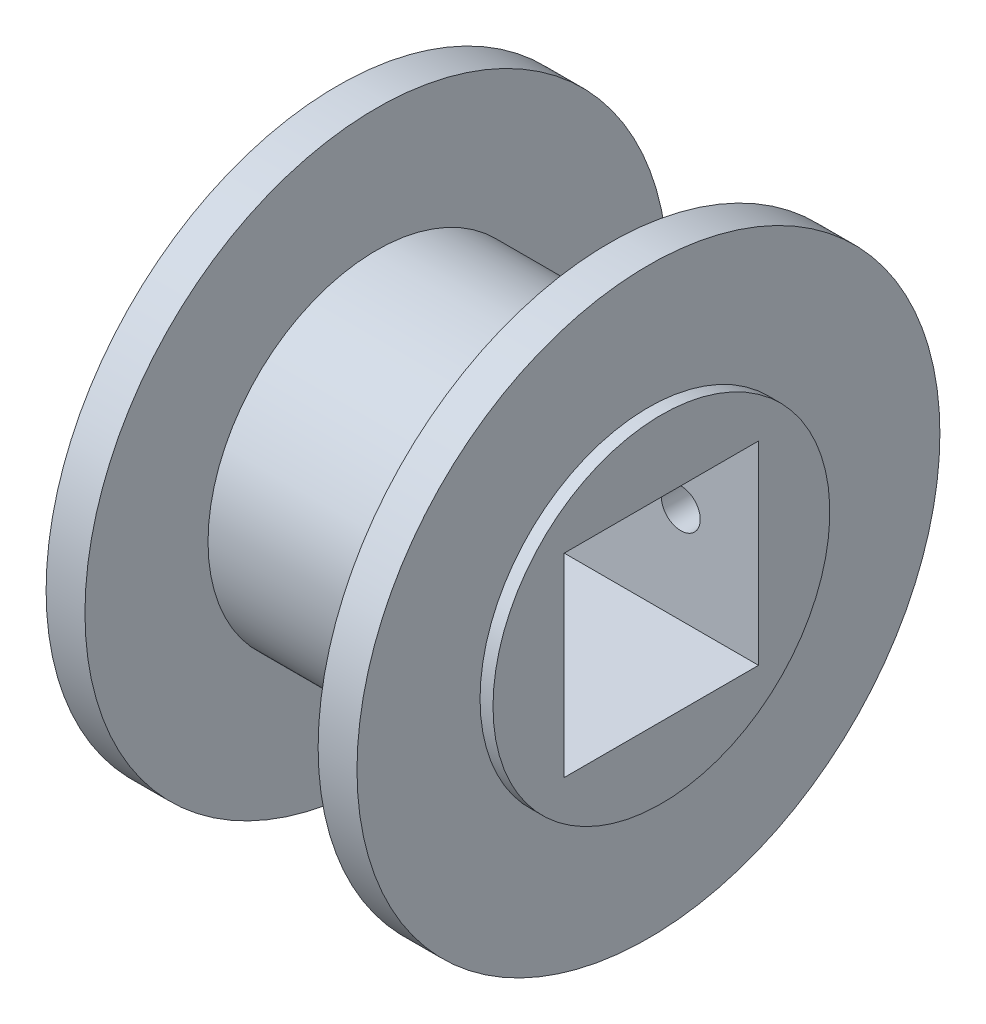
SolidWorks part; units mm, degrees
ref_plane "Front Plane" through (0, 0, 0) normal (0, 0, 1) x (1, 0, 0)
ref_plane "Top Plane" through (0, 0, 0) normal (0, 1, 0) x (1, 0, 0)
ref_plane "Right Plane" through (0, 0, 0) normal (1, 0, 0) x (0, 0, -1)
sketch "Sketch1" plane through (0, 0, 0) normal (0, 0, 1) x (1, 0, 0)
  line L0 (0, 0) -> (32.5033, 0) construction
  line L1 (0, 0) -> (0, 29.8727) construction
  line L2 (-13, -7.5) -> (13, -7.5) construction
  line L3 (-13, -7.5) -> (-13, 7.5) construction
  line L4 (-13, 7.5) -> (13, 7.5)
  line L5 (13, -7.5) -> (13, 7.5) construction
  line L6 (-13, -7.5) -> (13, 7.5) construction
  line L7 (-13, 7.5) -> (13, -7.5) construction
  line L8 (-13, 7.5) -> (-13, 13)
  line L9 (-13, 13) -> (-12, 13)
  line L10 (-12, 13) -> (-12, 22.5)
  line L11 (-12, 22.5) -> (-9, 22.5)
  line L12 (-9, 22.5) -> (-9, 13)
  line L13 (-9, 13) -> (9, 13)
  line L14 (13, 13) -> (12, 13)
  line L15 (13, 7.5) -> (13, 13)
  line L16 (12, 22.5) -> (9, 22.5)
  line L17 (12, 13) -> (12, 22.5)
  line L18 (9, 22.5) -> (9, 13)
  point P1 (0, 0)
  point P10 (-13, 10.25)
  point P20 (13, 10.25)
  point P24 (0, 13)
  dimension "D1" = 15
  dimension "D2" = 26
  dimension "D3" = 5.5
  dimension "D4" = 3
  dimension "D5" = 45
  dimension "D6" = 9
revolve "Revolve1" add sketch "Sketch1" angle 360 about L0
sketch "Sketch2" plane through (13, 0, 0) normal (1, 0, 0) x (0, 0, -1)
  line L1 (-7.5, -7.5) -> (7.5, -7.5)
  line L2 (-7.5, -7.5) -> (-7.5, 7.5)
  line L3 (-7.5, 7.5) -> (7.5, 7.5)
  line L4 (7.5, -7.5) -> (7.5, 7.5)
  line L5 (-7.5, -7.5) -> (7.5, 7.5) construction
  line L6 (-7.5, 7.5) -> (7.5, -7.5) construction
  point P0 (0, 0)
  dimension "D1" = 15
extrude "Cut-Extrude1" cut sketch "Sketch2" against normal through all
sketch "Sketch3" plane through (0, 0, 0) normal (0, 0, 1) x (1, 0, 0)
  line L0 (13, -7.5) -> (13, 7.5) construction
  line L1 (13, -7.5) -> (13, 7.5)
  line L2 (13, 0) -> (7, 0)
  circle A0 centre (7, 0) radius 1.5
  dimension "D2" = 3
  dimension "D1" = 6
extrude "Cut-Extrude2" cut sketch "Sketch3" against normal through all
